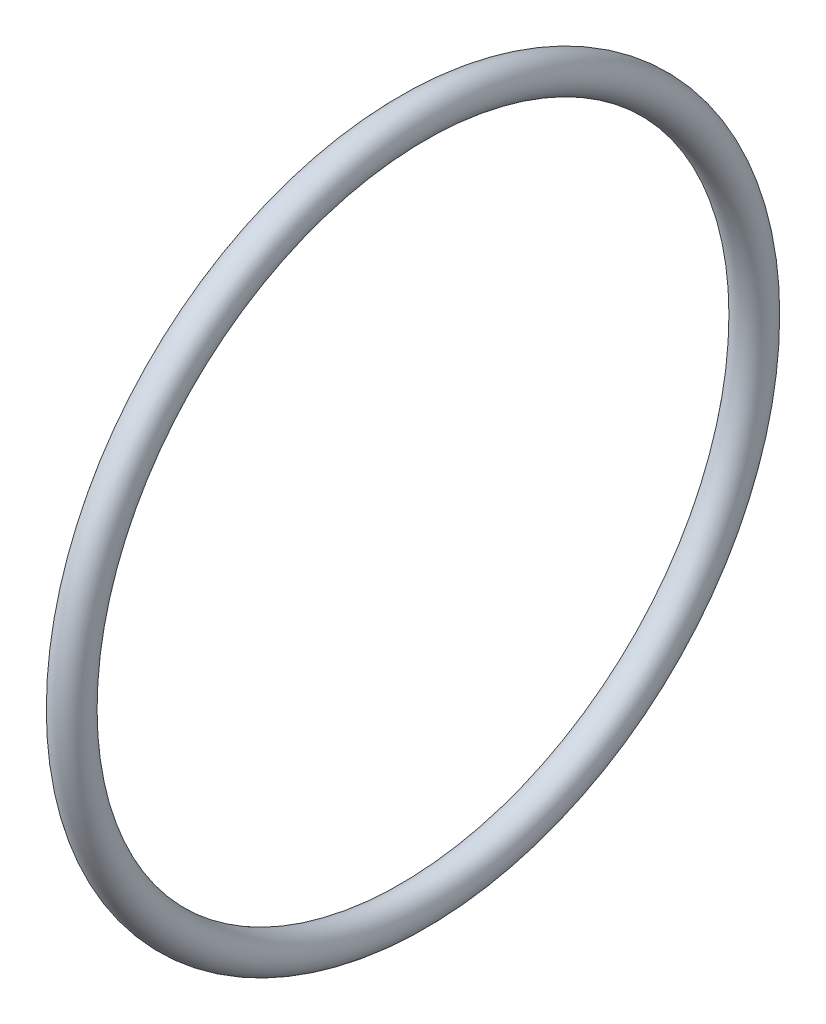
SolidWorks part; units mm, degrees
ref_plane "Front Plane" through (0, 0, 0) normal (0, 0, 1) x (1, 0, 0)
ref_plane "Top Plane" through (0, 0, 0) normal (0, 1, 0) x (1, 0, 0)
ref_plane "Right Plane" through (0, 0, 0) normal (1, 0, 0) x (0, 0, -1)
sketch "Sketch1" plane through (0, 0, 0) normal (0, 0, 1) x (1, 0, 0)
  line L0 (0, -1.5) -> (0, -28.5) construction
  line L1 (-2.6651, -28.5) -> (3.5672, -28.5) construction
  circle A0 centre (0, 0) radius 1.5
  dimension "D1" = 3
  dimension "D2" = 27
revolve "Revolve1" add sketch "Sketch1" angle 360 about L1
sketch "Sketch6" plane through (0, 0, 0) normal (0, 1, 0) x (1, 0, 0)
  line L0 (-1.5, 28.5) -> (-1.5, -28.5) construction
  line L1 (1.5, -28.5) -> (1.5, 28.5) construction
  line L2 (-1.5, 28.5) -> (-1.5, -28.5) construction
  line L3 (1.5, -28.5) -> (1.5, 28.5) construction
sketch "Sketch8" plane through (0, 0, 0) normal (1, 0, 0) x (0, 0, -1)
  circle A0 centre (0, -28.5) radius 30 construction
  circle A1 centre (0, -28.5) radius 27 construction
  circle A2 centre (0, -28.5) radius 30 construction
  circle A3 centre (0, -28.5) radius 27 construction
